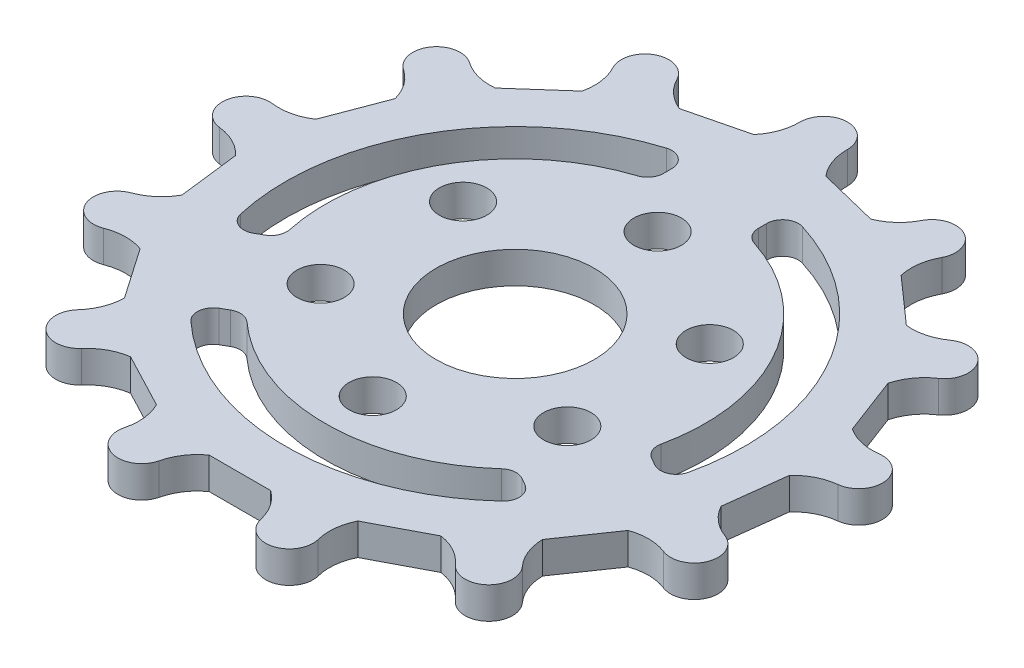
SolidWorks part; units mm, degrees
material "1060 Alloy"
ref_plane "Front Plane" through (0, 0, 0) normal (0, 0, 1) x (1, 0, 0)
ref_plane "Top Plane" through (0, 0, 0) normal (0, 1, 0) x (1, 0, 0)
ref_plane "Right Plane" through (0, 0, 0) normal (1, 0, 0) x (0, 0, -1)
sketch "Sketch1" plane through (0, 0, 0) normal (0, 1, 0) x (1, 0, 0)
  line L0 (0, 0) -> (9.2241, 0) construction
  line L1 (0, 0) -> (8.3653, 4.8297) construction
  line L2 (0, 22.5) -> (0, 19.5) construction
  line L3 (2.2759, 17.3514) -> (6.0484, 16.4216)
  line L4 (10.0788, 14.3062) -> (12.987, 11.7298)
  line L5 (15.5728, 7.9837) -> (16.9505, 4.3508)
  line L6 (17.4992, -0.1679) -> (17.0309, -4.0249)
  line L7 (15.4168, -8.2809) -> (13.2096, -11.4785)
  line L8 (9.8025, -14.4969) -> (6.3622, -16.3025)
  line L9 (1.9427, -17.3918) -> (-1.9427, -17.3918)
  line L10 (-6.3622, -16.3025) -> (-9.8025, -14.4969)
  line L11 (-13.2096, -11.4785) -> (-15.4168, -8.2809)
  line L12 (-17.0309, -4.0249) -> (-17.4992, -0.1679)
  line L13 (-16.9505, 4.3508) -> (-15.5728, 7.9837)
  line L14 (-12.987, 11.7298) -> (-10.0788, 14.3062)
  line L15 (-6.0484, 16.4216) -> (-2.2759, 17.3514)
  circle A0 centre (0, 0) radius 1.75
  circle A2 centre (0, 9) radius 1.5
  circle A3 centre (7.7942, -4.5) radius 1.5
  circle A4 centre (-7.7942, -4.5) radius 1.5
  circle A5 centre (7.7942, 4.5) radius 1.5
  circle A6 centre (0, -9) radius 1.5
  circle A7 centre (-7.7942, 4.5) radius 1.5
  arc A8 (1.4998, 19.4736) -> (-1.4998, 19.4736) centre (0, 19.5) ccw
  arc A9 (-1.5, 19.5) -> (-2.2759, 17.3514) centre (-4.7471, 19.4582) cw
  arc A10 (1.5, 19.5) -> (2.2759, 17.3514) centre (4.7471, 19.4582) ccw
  arc A11 (7.7339, 17.9635) -> (6.0484, 16.4216) centre (4.8393, 19.4355) cw
  arc A12 (10.3778, 16.546) -> (7.7218, 17.94) centre (9.0621, 17.2664) ccw
  arc A13 (10.3903, 16.5693) -> (10.0788, 14.3062) centre (13.246, 15.0233) ccw
  arc A14 (15.1961, 12.3117) -> (12.987, 11.7298) centre (13.3171, 14.9603) cw
  arc A15 (16.8784, 9.828) -> (15.1745, 12.2965) centre (16.0482, 11.0773) ccw
  arc A16 (16.9003, 9.8428) -> (15.5728, 7.9837) centre (18.7104, 7.1467) ccw
  arc A17 (19.177, 3.8395) -> (16.9505, 4.3508) centre (18.7441, 7.0579) cw
  arc A18 (19.5124, 0.8584) -> (19.1508, 3.8361) centre (19.3578, 2.3505) ccw
  arc A19 (19.5386, 0.8614) -> (17.4992, -0.1679) centre (19.8885, -2.3671) ccw
  arc A20 (18.7647, -5.5123) -> (17.0309, -4.0249) centre (19.8771, -2.4614) cw
  arc A21 (17.6763, -8.3077) -> (18.7399, -5.5031) centre (18.2328, -6.9148) ccw
  arc A22 (17.7009, -8.3173) -> (15.4168, -8.2809) centre (16.5104, -11.3386) ccw
  arc A23 (14.0537, -13.6013) -> (13.2096, -11.4785) centre (16.4564, -11.4168) cw
  arc A24 (11.7908, -15.5707) -> (14.036, -13.5817) centre (12.9309, -14.596) ccw
  arc A25 (11.8081, -15.5906) -> (9.8025, -14.4969) centre (9.3499, -17.7126) ccw
  arc A26 (6.1231, -18.5744) -> (6.3622, -16.3025) centre (9.2658, -17.7567) cw
  arc A27 (3.2041, -19.2666) -> (6.1165, -18.5488) centre (4.6667, -18.9334) ccw
  arc A28 (3.2102, -19.2923) -> (1.9427, -17.3918) centre (0.0475, -20.0288) ccw
  arc A29 (-3.2102, -19.2923) -> (-1.9427, -17.3918) centre (-0.0475, -20.0288) cw
  arc A30 (-6.1165, -18.5488) -> (-3.2041, -19.2666) centre (-4.6667, -18.9334) ccw
  arc A31 (-6.1231, -18.5744) -> (-6.3622, -16.3025) centre (-9.2658, -17.7567) ccw
  arc A32 (-11.8081, -15.5906) -> (-9.8025, -14.4969) centre (-9.3499, -17.7126) cw
  arc A33 (-14.036, -13.5817) -> (-11.7908, -15.5707) centre (-12.9309, -14.596) ccw
  arc A34 (-14.0537, -13.6013) -> (-13.2096, -11.4785) centre (-16.4564, -11.4168) ccw
  arc A35 (-17.7009, -8.3173) -> (-15.4168, -8.2809) centre (-16.5104, -11.3386) cw
  arc A36 (-18.7399, -5.5031) -> (-17.6763, -8.3077) centre (-18.2328, -6.9148) ccw
  arc A37 (-18.7647, -5.5123) -> (-17.0309, -4.0249) centre (-19.8771, -2.4614) ccw
  arc A38 (-19.5386, 0.8614) -> (-17.4992, -0.1679) centre (-19.8885, -2.3671) cw
  arc A39 (-19.1508, 3.8361) -> (-19.5124, 0.8584) centre (-19.3578, 2.3505) ccw
  arc A40 (-19.177, 3.8395) -> (-16.9505, 4.3508) centre (-18.7441, 7.0579) ccw
  arc A41 (-16.9003, 9.8428) -> (-15.5728, 7.9837) centre (-18.7104, 7.1467) cw
  arc A42 (-15.1745, 12.2965) -> (-16.8784, 9.828) centre (-16.0482, 11.0773) ccw
  arc A43 (-15.1961, 12.3117) -> (-12.987, 11.7298) centre (-13.3171, 14.9603) ccw
  arc A44 (-10.3903, 16.5693) -> (-10.0788, 14.3062) centre (-13.246, 15.0233) cw
  arc A45 (-7.7218, 17.94) -> (-10.3778, 16.546) centre (-9.0621, 17.2664) ccw
  arc A46 (-7.7339, 17.9635) -> (-6.0484, 16.4216) centre (-4.8393, 19.4355) ccw
  point P13 (0, 0)
  point P22 (0, 0)
  point P28 (0, 21)
  point P140 (0, 0)
  point P165 (0, 0)
  dimension "D1" = 3.5
  dimension "D2" = 13
  dimension "D3" = 3
  dimension "D4" = 9
  dimension "D7" = 3
  dimension "D8" = 9
  dimension "D10" = 3
  dimension "D11" = 19.5
  dimension "D12" = 13
  dimension "D6" = 30
  dimension "D5" = 3
  dimension "D9" = 3
extrude "Boss-Extrude3" add sketch "Sketch1" along normal blind 2 contours A46 A45 A44 L14 A43 A42 A41 L13 A40 A39 A38 L12 A37 A36 A35 L11 A34 A33 A32 L10 A31 A30 A29 L9 A28 A27 A26 L8 A25 A24 A23 L7 A22 A21 A20
sketch "Sketch3" plane through (0, 2, 0) normal (0, 1, 0) x (1, 0, 0)
  line L0 (-3, 14.1863) -> (-3, 11.619)
  line L1 (3, 14.1863) -> (3, 11.619)
  line L2 (13.7857, -4.4951) -> (11.5623, -3.2114)
  line L3 (10.7857, -9.6912) -> (8.5623, -8.4076)
  line L4 (-10.7857, -9.6912) -> (-8.5623, -8.4076)
  line L5 (-13.7857, -4.4951) -> (-11.5623, -3.2114)
  arc A0 (-3, 11.619) -> (-11.5623, -3.2114) centre (0, 0) ccw
  arc A1 (-3, 14.1863) -> (-13.7857, -4.4951) centre (0, 0) ccw
  circle A2 centre (0, 9) radius 1.5 construction
  arc A3 (-8.5623, -8.4076) -> (8.5623, -8.4076) centre (0, 0) ccw
  arc A4 (-10.7857, -9.6912) -> (10.7857, -9.6912) centre (0, 0) ccw
  arc A5 (11.5623, -3.2114) -> (3, 11.619) centre (0, 0) ccw
  arc A6 (13.7857, -4.4951) -> (3, 14.1863) centre (0, 0) ccw
  point P20 (0, 0)
  dimension "D1" = 24
  dimension "D2" = 29
  dimension "D3" = 3
  dimension "D4" = 3
  dimension "D5" = 3
extrude "Cut-Extrude1" cut sketch "Sketch3" against normal blind 2
fillet "Fillet1" radius 1 12 edges at (-13.7857, 1, 4.4951) (-10.7857, 1, 9.6912) (8.5623, 1, 8.4076) (-3, 1, -14.1863) (-8.5623, 1, 8.4076) (10.7857, 1, 9.6912) (-11.5623, 1, 3.2114) (-3, 1, -11.619) (13.7857, 1, 4.4951) (11.5623, 1, 3.2114) (3, 1, -11.619) (3, 1, -14.1863)
sketch "Sketch4" plane through (0, 2, 0) normal (0, 1, 0) x (1, 0, 0)
  circle A0 centre (0, 0) radius 5
  dimension "D1" = 10
extrude "Cut-Extrude2" cut sketch "Sketch4" against normal blind 10
